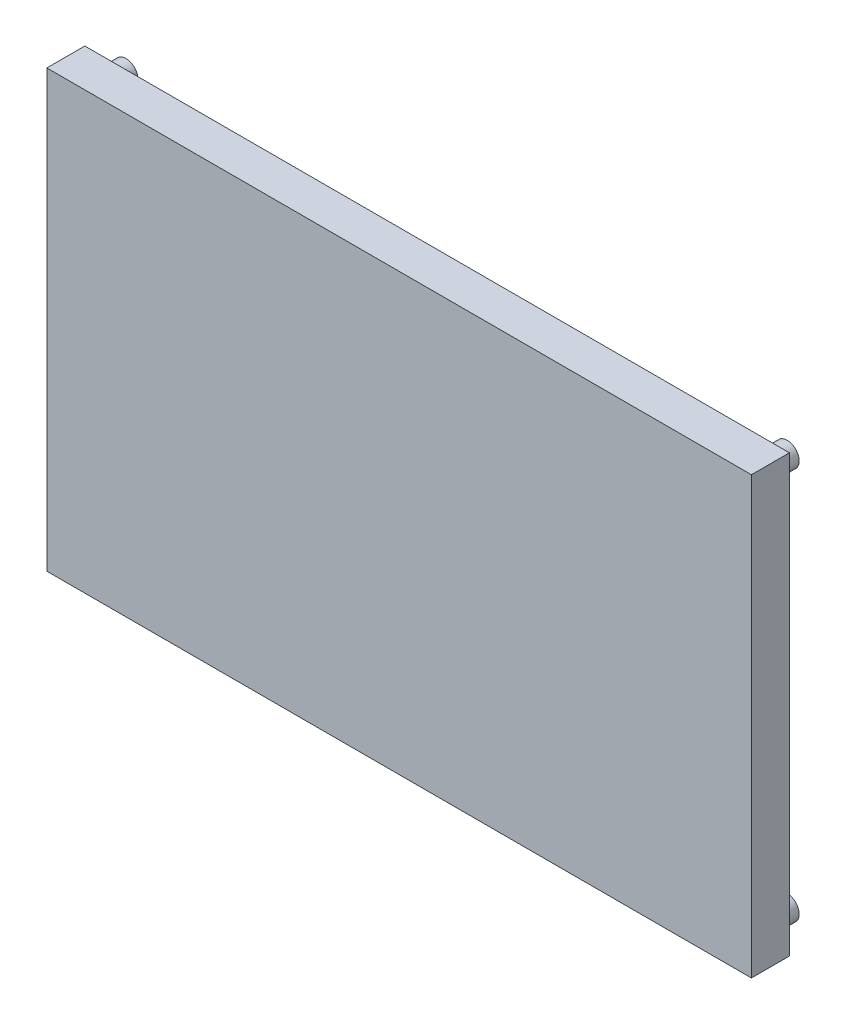
SolidWorks part; units mm, degrees
ref_plane "Front Plane" through (0, 0, 0) normal (0, 0, 1) x (1, 0, 0)
ref_plane "Top Plane" through (0, 0, 0) normal (0, 1, 0) x (1, 0, 0)
ref_plane "Right Plane" through (0, 0, 0) normal (1, 0, 0) x (0, 0, -1)
sketch "Sketch1" plane through (0, 0, 0) normal (0, 0, 1) x (1, 0, 0)
  line L1 (82.445, -51) -> (-82.445, -51)
  line L2 (82.445, -51) -> (82.445, 51)
  line L3 (82.445, 51) -> (-82.445, 51)
  line L4 (-82.445, -51) -> (-82.445, 51)
  line L5 (82.445, -51) -> (-82.445, 51) construction
  line L6 (82.445, 51) -> (-82.445, -51) construction
  point P0 (0, 0)
  dimension "D1" = 164.89
  dimension "D2" = 102
extrude "Boss-Extrude1" add sketch "Sketch1" against normal blind 8.89
sketch "Sketch2" plane through (0, 0, -8.89) normal (0, 0, -1) x (-1, 0, 0)
  line L0 (-90.5849, 45.92) -> (82.445, 45.92) construction
  line L1 (82.445, 51) -> (82.445, -51) construction
  line L2 (-77.365, 51) -> (-77.365, -51) construction
  line L3 (-82.445, 51) -> (82.445, 51) construction
  line L4 (82.445, -51) -> (-82.445, -51) construction
  line L5 (-82.445, -45.92) -> (82.445, -45.92) construction
  line L6 (-82.445, -51) -> (-82.445, 51) construction
  line L7 (77.365, 51) -> (77.365, -51) construction
  circle A0 centre (-77.365, 45.92) radius 2.794
  circle A1 centre (77.365, 45.92) radius 2.794
  circle A2 centre (-77.365, -45.92) radius 2.794
  circle A3 centre (77.365, -45.92) radius 2.794
  dimension "D5" = 5.588
  dimension "D1" = 5.08
  dimension "D2" = 5.08
  dimension "D3" = 5.08
  dimension "D4" = 5.08
extrude "Boss-Extrude2" add sketch "Sketch2" along normal blind 4.572
sketch "Sketch3" plane through (0, 0, -8.89) normal (0, 0, -1) x (-1, 0, 0)
  line L0 (-18.945, -33.22) -> (20.557, -33.22) construction
  line L5 (23.351, -33.22) -> (23.351, -51) construction
  line L6 (-18.945, 15.78) -> (82.445, 15.78) construction
  line L8 (-82.445, 15.78) -> (-21.739, 15.78) construction
  line L9 (-82.445, -51) -> (-82.445, 51) construction
  line L10 (82.445, 51) -> (82.445, -51) construction
  line L11 (-82.445, -33.22) -> (-21.739, -33.22) construction
  line L12 (-21.739, 51) -> (-21.739, 15.78) construction
  line L13 (-82.445, 51) -> (82.445, 51) construction
  line L14 (82.445, -51) -> (-82.445, -51) construction
  line L15 (23.351, -51) -> (23.351, -33.22) construction
  line L16 (-82.445, 15.78) -> (-21.739, 15.78) construction
  line L17 (23.351, -30.426) -> (23.351, 51) construction
  line L18 (-21.739, 12.986) -> (-21.739, -30.426) construction
  line L19 (-21.739, -33.22) -> (-21.739, -51) construction
  line L20 (23.351, -33.22) -> (82.445, -33.22) construction
  circle A0 centre (-21.739, 15.78) radius 2.794
  circle A2 centre (-21.739, -33.22) radius 2.794
  circle A3 centre (23.351, -33.22) radius 2.794
  circle A4 centre (23.351, 15.78) radius 2.794
  dimension "D3" = 5.588
  dimension "D1" = 59.094
  dimension "D2" = 49
  dimension "D4" = 17.78
  dimension "D5" = 60.706
extrude "Boss-Extrude3" add sketch "Sketch3" along normal blind 5.588
